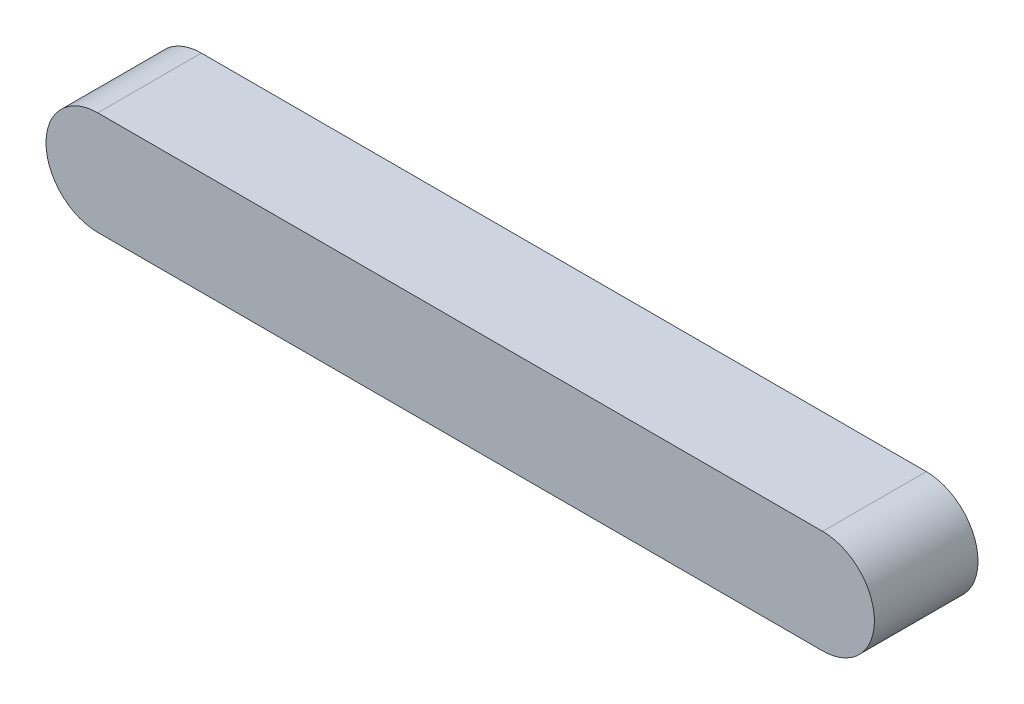
SolidWorks part; units mm, degrees
ref_plane "Front Plane" through (0, 0, 0) normal (0, 0, 1) x (1, 0, 0)
ref_plane "Top Plane" through (0, 0, 0) normal (0, 1, 0) x (1, 0, 0)
ref_plane "Right Plane" through (0, 0, 0) normal (1, 0, 0) x (0, 0, -1)
sketch "Sketch1" plane through (0, 0, 0) normal (0, 1, 0) x (1, 0, 0)
  line L0 (-12.7, 0) -> (12.7, 0) construction
  line L1 (-12.7, 1.5875) -> (12.7, 1.5875)
  line L2 (-12.7, 1.5875) -> (-12.7, -1.5875)
  line L3 (-12.7, -1.5875) -> (12.7, -1.5875)
  line L4 (12.7, 1.5875) -> (12.7, -1.5875)
  dimension "Square Size" = 3.175
  dimension "Length" = 25.4
extrude "Extrude1" add sketch "Sketch1" against normal blind 3.175
sketch "Sketch2" plane through (44.45, 6.35, 1.5875) normal (0, 0, -1) x (-1, 0, 0)
  line L0 (33.3375, -7.9375) -> (55.5625, -7.9375) construction
  line L1 (33.3375, -6.35) -> (55.5625, -6.35)
  line L2 (33.3375, -9.525) -> (55.5625, -9.525)
  line L5 (57.15, -7.9375) -> (55.5625, -7.9375) construction
  line L6 (33.3375, -7.9375) -> (31.75, -7.9375) construction
  line L7 (31.75, -9.525) -> (31.75, -6.35) construction
  line L8 (57.15, -9.525) -> (57.15, -6.35) construction
  line L9 (31.75, -6.35) -> (57.15, -6.35) construction
  arc A0 (33.3375, -6.35) -> (33.3375, -9.525) centre (33.3375, -7.9375) ccw
  arc A1 (55.5625, -9.525) -> (55.5625, -6.35) centre (55.5625, -7.9375) ccw
  point P2 (44.45, -7.9375)
extrude "Extrude2" cut sketch "Sketch2" along normal through all flip side to cut
sketch "Sketch3" plane through (0, 0, 0) normal (0, 1, 0) x (1, 0, 0)
  line L0 (0, -1.5875) -> (0, 1.5875) construction
  line L1 (-11.1125, -1.5875) -> (11.1125, -1.5875) construction
  line L2 (11.1125, 1.5875) -> (-11.1125, 1.5875) construction
  dimension "D1" = 3.175
